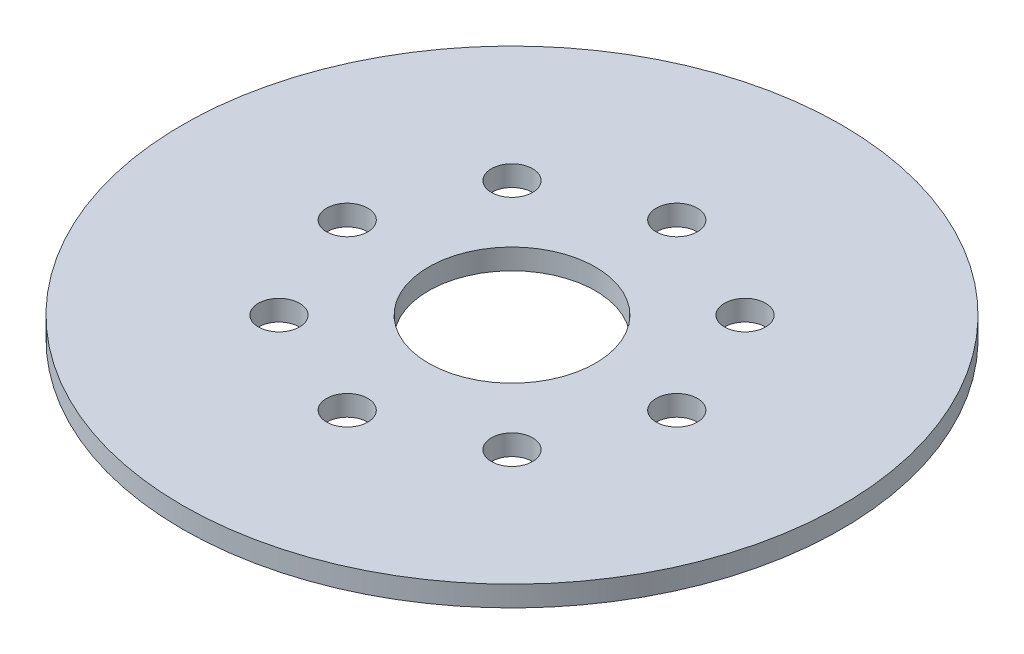
SolidWorks part; units mm, degrees
material "ABS PC"
ref_plane "Front Plane" through (0, 0, 0) normal (0, 0, 1) x (1, 0, 0)
ref_plane "Top Plane" through (0, 0, 0) normal (0, 1, 0) x (1, 0, 0)
ref_plane "Right Plane" through (0, 0, 0) normal (1, 0, 0) x (0, 0, -1)
sketch "Sketch1" plane through (0, 0, 0) normal (0, 1, 0) x (1, 0, 0)
  circle A1 centre (0, 0) radius 4.05
  circle A2 centre (0, 0) radius 16
  circle A3 centre (0, 8) radius 1
  circle A4 centre (5.6569, 5.6569) radius 1
  circle A5 centre (8, 0) radius 1
  circle A6 centre (5.6569, -5.6569) radius 1
  circle A7 centre (0, -8) radius 1
  circle A8 centre (-5.6569, -5.6569) radius 1
  circle A9 centre (-8, 0) radius 1
  circle A10 centre (-5.6569, 5.6569) radius 1
  point P1 (0, 8.9449)
  dimension "D1" = 8
  dimension "D2" = 8
  dimension "D3" = 8.1
  dimension "D4" = 2
extrude "Boss-Extrude1" add sketch "Sketch1" along normal blind 1
